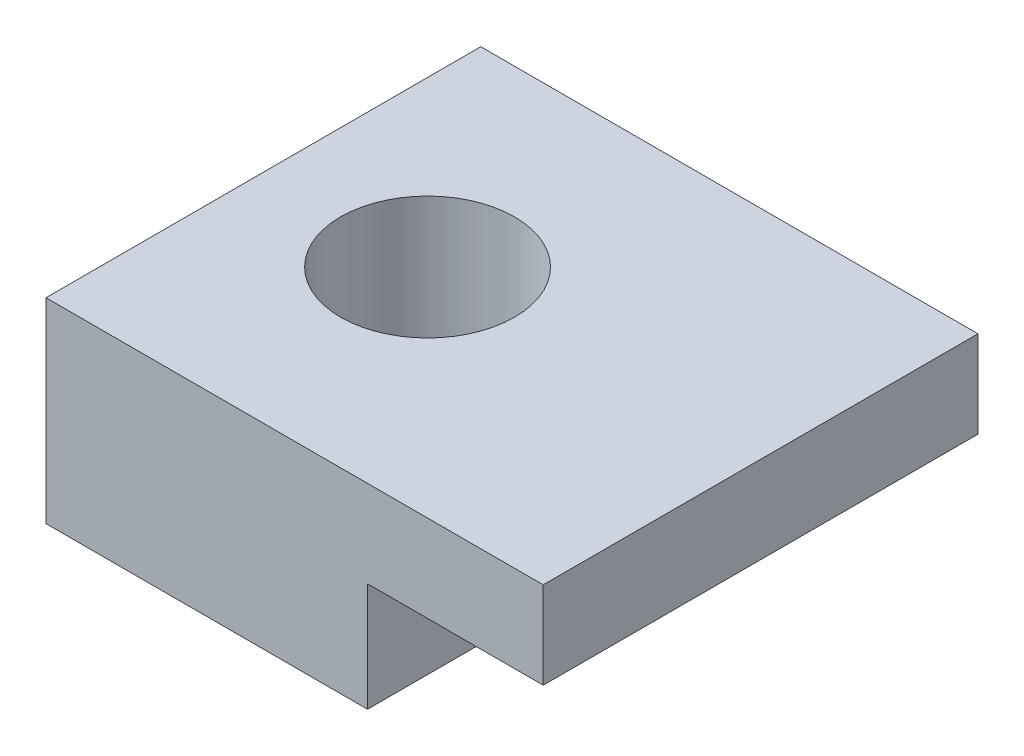
SolidWorks part; units mm, degrees
ref_plane "Płaszczyzna przednia" through (0, 0, 0) normal (0, 0, 1) x (1, 0, 0)
ref_plane "Płaszczyzna górna" through (0, 0, 0) normal (0, 1, 0) x (1, 0, 0)
ref_plane "Płaszczyzna prawa" through (0, 0, 0) normal (1, 0, 0) x (0, 0, -1)
sketch "Sketch1" plane through (0, 0, 0) normal (0, 0, 1) x (1, 0, 0)
  line L2 (-3.7763, 0) -> (-3.7763, 4.5)
  line L3 (-3.7763, 4.5) -> (7.6602, 4.5)
  line L4 (7.6602, 4.5) -> (7.6602, 2.5)
  line L5 (7.6602, 2.5) -> (3.6188, 2.5)
  line L6 (3.6188, 2.5) -> (3.6188, 0)
  line L7 (3.6188, 0) -> (-3.7763, 0)
  dimension "D1" = 2.5
  dimension "D2" = 4.5
extrude "Boss-Extrude1" add sketch "Sketch1" along normal blind 10
sketch "Sketch2" plane through (0, 4.5, 0) normal (0, 1, 0) x (1, 0, 0)
  line L0 (-3.7763, -5) -> (7.6602, -5) construction
  line L1 (-3.7763, -10) -> (-3.7763, 0) construction
  line L2 (7.6602, -10) -> (7.6602, 0) construction
  circle A0 centre (0, -5) radius 2
  dimension "D1" = 4
extrude "Cut-Extrude1" cut sketch "Sketch2" against normal blind 10
